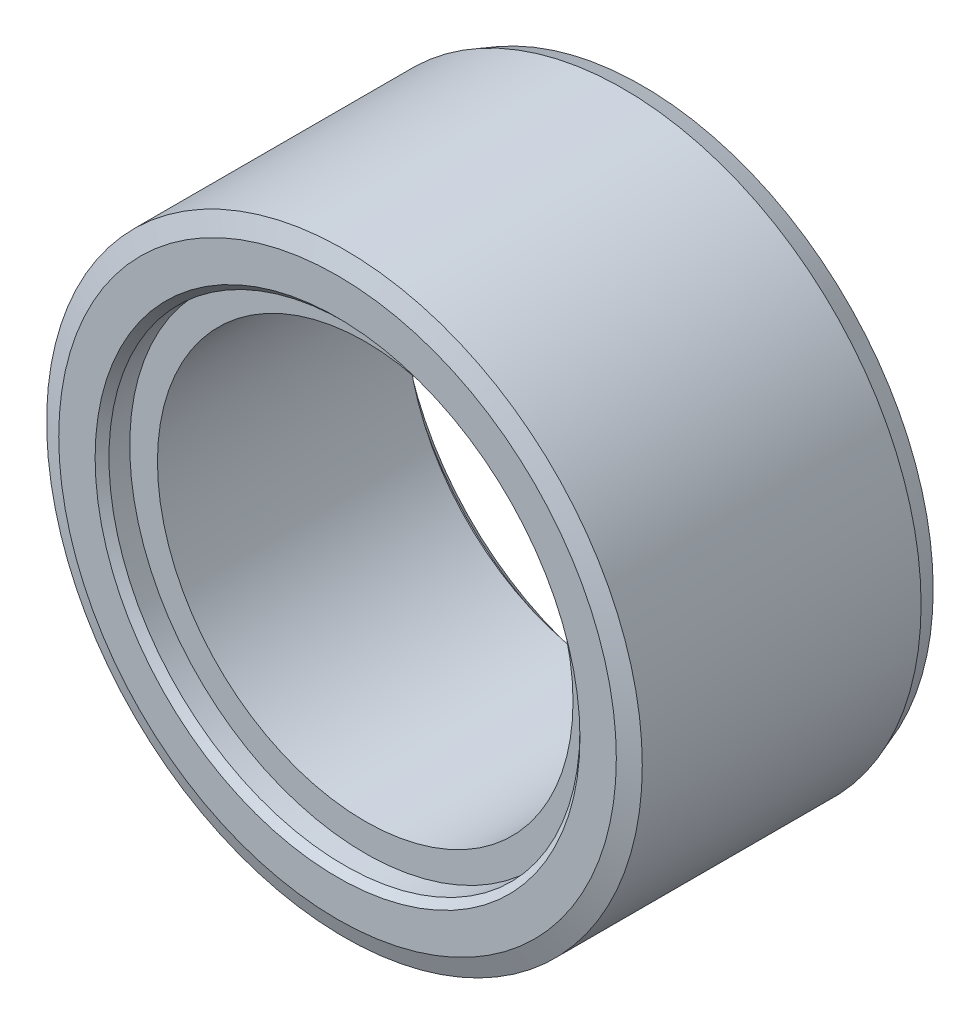
SolidWorks part; units mm, degrees
ref_plane "Front Plane" through (0, 0, 0) normal (0, 0, 1) x (1, 0, 0)
ref_plane "Top Plane" through (0, 0, 0) normal (0, 1, 0) x (1, 0, 0)
ref_plane "Right Plane" through (0, 0, 0) normal (1, 0, 0) x (0, 0, -1)
sketch "Sketch1" plane through (0, 0, 0) normal (0, 0, 1) x (1, 0, 0)
  circle A0 centre (0, 0) radius 21.5
  dimension "D1" = 43
extrude "Boss-Extrude1" add sketch "Sketch1" along normal blind 22
sketch "Sketch3" plane through (0, 0, 22) normal (0, 0, 1) x (1, 0, 0)
  circle A0 centre (0, 0) radius 15
  dimension "D1" = 30
extrude "Cut-Extrude1" cut sketch "Sketch3" against normal up to surface (22 mm away) up to face at (21.5, 0, 0)
sketch "Sketch4" plane through (0, 0, 22) normal (0, 0, 1) x (1, 0, 0)
  circle A0 centre (0, 0) radius 17
  circle A1 centre (0, 0) radius 15 construction
  dimension "D1" = 2
extrude "Cut-Extrude2" cut sketch "Sketch4" against normal blind 2
sketch "Sketch5" plane through (0, 0, 0) normal (0, 0, -1) x (-1, 0, 0)
  circle A0 centre (0, 0) radius 17
  circle A1 centre (0, 0) radius 15 construction
  dimension "D1" = 2
extrude "Cut-Extrude3" cut sketch "Sketch5" against normal blind 2
chamfer "Chamfer1" distance 0.5 angle 45 2 edges at (17, 0, 22) (-17, 0, 0)
chamfer "Chamfer3" distance 0.5 angle 70 1 edges at (21.5, 0, 0)
chamfer "Chamfer5" distance 0.5 angle 70 1 edges at (21.5, 0, 22)
